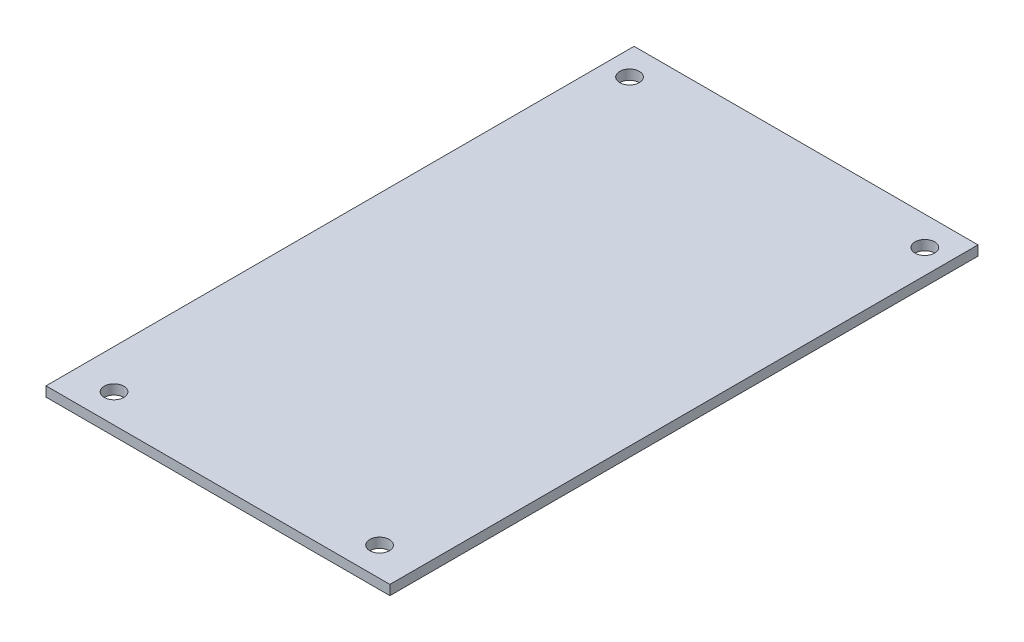
SolidWorks part; units mm, degrees
ref_plane "Front Plane" through (0, 0, 0) normal (0, 0, 1) x (1, 0, 0)
ref_plane "Top Plane" through (0, 0, 0) normal (0, 1, 0) x (1, 0, 0)
ref_plane "Right Plane" through (0, 0, 0) normal (1, 0, 0) x (0, 0, -1)
sketch "Sketch1" plane through (0, 0, 0) normal (0, 1, 0) x (1, 0, 0)
  line L1 (0, 0) -> (55.7022, 0)
  line L2 (0, 0) -> (0, 95.25)
  line L3 (0, 95.25) -> (55.7022, 95.25)
  line L4 (55.7022, 0) -> (55.7022, 95.25)
  dimension "D1" = 95.25
  dimension "D2" = 55.7022
extrude "Boss-Extrude1" add sketch "Sketch1" along normal blind 1.5875
sketch "Sketch2" plane through (0, 1.5875, 0) normal (0, 1, 0) x (1, 0, 0)
  line L0 (3.937, 90.5764) -> (51.7652, 90.5764) construction
  line L1 (6.35, 4.6736) -> (49.3522, 4.6736) construction
  line L2 (27.8511, 95.25) -> (27.8511, 0) construction
  line L3 (55.7022, 95.25) -> (0, 95.25) construction
  line L4 (0, 0) -> (55.7022, 0) construction
  line L5 (0, 95.25) -> (0, 0) construction
  circle A0 centre (3.937, 90.5764) radius 1.5875
  circle A1 centre (51.7652, 90.5764) radius 1.5875
  circle A2 centre (6.35, 4.6736) radius 1.5875
  circle A3 centre (49.3522, 4.6736) radius 1.5875
  point P8 (0, 0)
  point P15 (27.8511, 4.6736)
  point P16 (27.8511, 90.5764)
  point P19 (0, 0)
  point P20 (51.6766, 92.0948)
  dimension "D1" = 3.175
  dimension "D2" = 3.937
  dimension "D3" = 90.5764
  dimension "D4" = 6.35
  dimension "D5" = 4.6736
extrude "Cut-Extrude1" cut sketch "Sketch2" against normal through all
